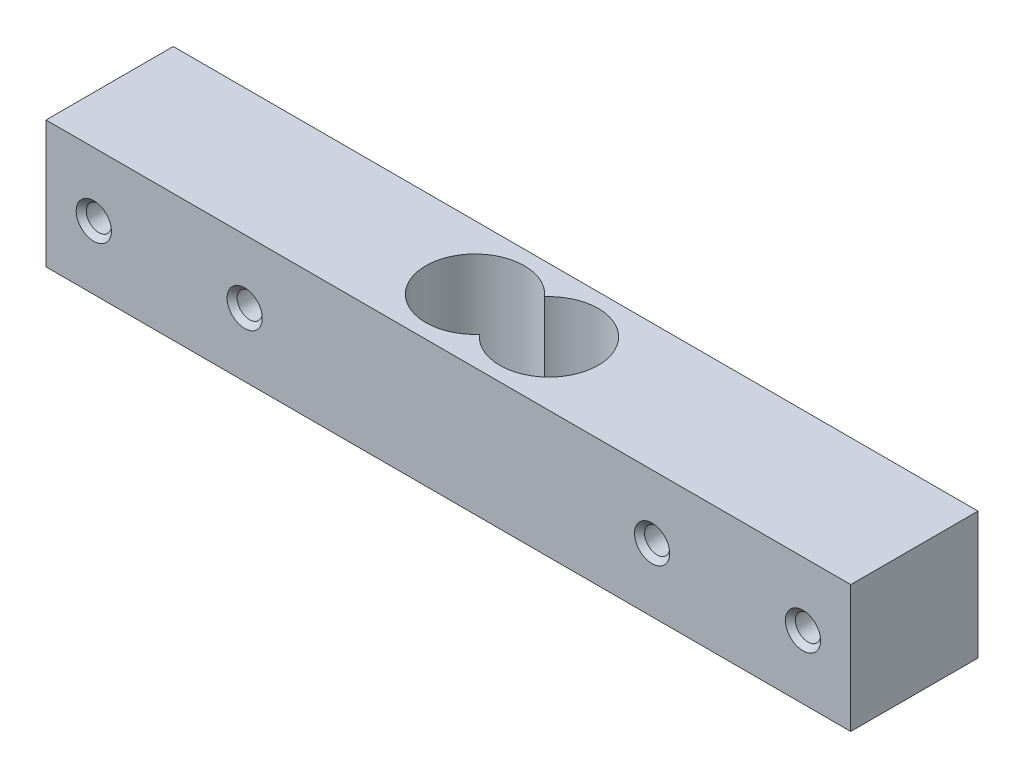
SolidWorks part; units mm, degrees
ref_plane "Front Plane" through (0, 0, 0) normal (0, 0, 1) x (1, 0, 0)
ref_plane "Top Plane" through (0, 0, 0) normal (0, 1, 0) x (1, 0, 0)
ref_plane "Right Plane" through (0, 0, 0) normal (1, 0, 0) x (0, 0, -1)
sketch "Sketch1" plane through (0, 0, 0) normal (0, 1, 0) x (1, 0, 0)
  line L0 (0, 0) -> (0, 50927.2988) construction
  line L1 (-40, -6.325) -> (40, -6.325)
  line L2 (-40, -6.325) -> (-40, 6.325)
  line L3 (-40, 6.325) -> (40, 6.325)
  line L4 (40, -6.325) -> (40, 6.325)
  line L5 (-40, -6.325) -> (40, 6.325) construction
  line L6 (-40, 6.325) -> (40, -6.325) construction
  circle A0 centre (-3.675, 0) radius 4.9
  circle A1 centre (3.675, 0) radius 4.9
  point P0 (0, 0)
  dimension "D1" = 9.8
  dimension "D2" = 12.65
  dimension "D3" = 80
  dimension "D4" = 7.35
extrude "Boss-Extrude1" add sketch "Sketch1" along normal mid plane 12.65 contours L1 L4 L3 L2 A1 A0
sketch "Sketch2" plane through (0, 0, -6.325) normal (0, 0, -1) x (-1, 0, 0)
  line L0 (-35.25, 0) -> (-20.25, 0) construction
  line L1 (-20.25, 0) -> (20.25, 0) construction
  line L2 (20.25, 0) -> (35.25, 0) construction
  point P6 (0, 0)
  dimension "D1" = 70.5
  dimension "D2" = 40.5
hole_wizard "M3 Tapped Hole1" positions "Sketch3" profile "Sketch5" tap size "M3" standard "DIN" end condition through all
sketch "Sketch3" plane through (0, 0, -6.325) normal (0, 0, -1) x (-1, 0, 0)
  point P0 (35.25, 0)
  point P3 (20.25, 0)
  point P6 (-20.25, 0)
  point P9 (-35.25, 0)
cosmetic thread "Hole Thread1" parameters "D2"=3
cosmetic thread "Hole Thread2" parameters "D2"=3
cosmetic thread "Hole Thread3" parameters "D2"=3
cosmetic thread "Hole Thread4" parameters "D2"=3
sketch "Sketch5" plane through (-35.25, 0, -6.325) normal (1, 0, 0) x (0, 1, 0)
  line L0 (0, 0) -> (0, 12.65)
  line L1 (0, 12.65) -> (1.75, 12.65)
  line L2 (1.25, 12.15) -> (1.25, 0.5)
  line L3 (1.25, 0.5) -> (1.75, 0)
  line L5 (1.75, 0) -> (0, 0)
  line L6 (-1.25, 0.5) -> (-1.75, 0) construction
  line L7 (1.75, 12.65) -> (1.25, 12.15)
  line L8 (-1.75, 12.65) -> (-1.25, 12.15) construction
  line L11 (0, -6.35) -> (0, 107.95) construction
  dimension "Thru Tap Drill Dia." = 2.5
  dimension "Thru Tap Drill Depth" = 12.65
  dimension "Near C'Sink Dia." = 3.5
  dimension "Near C'Sink Angle" = 90
  dimension "Far C'Sink Dia." = 3.5
  dimension "Far C'Sink Angle" = 90
scale "Scale1" scale about centroid uniform scaling yes scale factor 3
